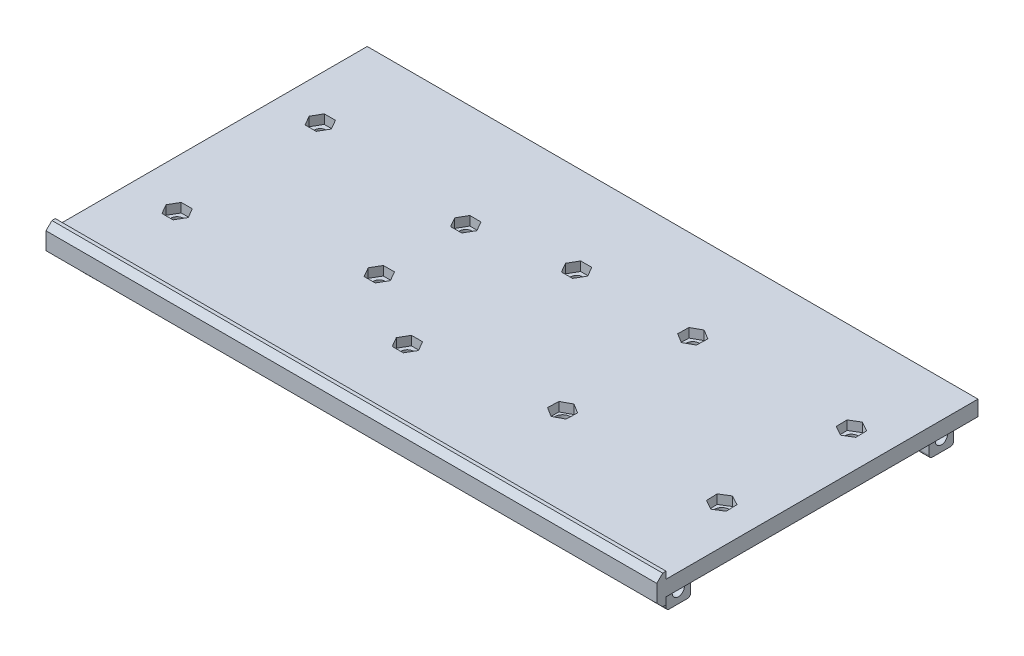
SolidWorks part; units mm, degrees
ref_plane "Alzado" through (0, 0, 0) normal (0, 0, 1) x (1, 0, 0)
ref_plane "Planta" through (0, 0, 0) normal (0, 1, 0) x (1, 0, 0)
ref_plane "Vista lateral" through (0, 0, 0) normal (1, 0, 0) x (0, 0, -1)
sketch "Croquis3" plane through (0, 0, 0) normal (0, 1, 0) x (1, 0, 0)
  line L1 (-116.001, 50) -> (83.999, 50)
  line L2 (-116.001, 50) -> (-116.001, -50)
  line L3 (-116.001, -50) -> (83.999, -50)
  line L4 (83.999, 50) -> (83.999, -50)
  circle A0 centre (19.4896, 21.1007) radius 2.45
  circle A1 centre (71.658, 20.902) radius 2.45
  circle A2 centre (71.3776, -21.3107) radius 2.45
  circle A3 centre (19.1425, -21.1883) radius 2.4502
  dimension "D4" = 4.9
  dimension "D5" = 4.9
  dimension "D6" = 4.9
  dimension "D1" = 100
  dimension "D2" = 50
  dimension "D3" = 200
extrude "Saliente-Extruir1" add sketch "Croquis3" along normal blind 5
sketch "Croquis23" plane through (0, 0, 0) normal (0, 1, 0) x (1, 0, 0)
  line L0 (-116.001, 50) -> (-116.001, -50) construction
  line L1 (-116.001, 23.3955) -> (-13.501, 23.3955) construction
  line L2 (-116.001, 23.3955) -> (-116.001, -30.6045) construction
  line L3 (-116.001, -30.6045) -> (-13.501, -30.6045) construction
  line L4 (-13.501, 23.3955) -> (-13.501, -30.6045) construction
  line L5 (83.999, 50) -> (-116.001, 50) construction
  dimension "D1" = 54
  dimension "D2" = 102.5
  dimension "D3" = 26.6045
sketch "Croquis24" plane through (0, 0, 0) normal (0, 1, 0) x (1, 0, 0)
  circle A0 centre (-18.4173, 20.98) radius 1.9594
  circle A1 centre (-25.0227, -27.8259) radius 1.9784
  circle A2 centre (-49.4418, -12.6126) radius 1.963
  circle A3 centre (-49.4418, 15.7151) radius 2.1255
  circle A4 centre (-102.0965, 20.7097) radius 1.8726
  circle A5 centre (-100.4246, -27.8259) radius 2.0276
sketch "Croquis4" plane through (0, 5, 0) normal (0, 1, 0) x (1, 0, 0)
  circle A0 centre (-18.4173, 20.98) radius 1.9594
  circle A1 centre (-49.4418, 15.7151) radius 2.1255
  circle A2 centre (-49.4418, -12.6126) radius 1.963
  circle A3 centre (-25.0227, -27.8259) radius 1.9784
  circle A4 centre (-100.4246, -27.8259) radius 2.0276
  circle A5 centre (-102.0965, 20.7097) radius 1.8726
  circle A6 centre (-102.0965, 20.7097) radius 3.3726
  circle A7 centre (-100.4246, -27.8259) radius 3.5276
  circle A8 centre (-49.4418, -12.6126) radius 3.463
  circle A9 centre (-25.0227, -27.8259) radius 3.4784
  circle A10 centre (-18.4173, 20.98) radius 3.4594
  circle A11 centre (-49.4418, 15.7151) radius 3.6255
  circle A95 centre (19.4896, 21.1007) radius 2.1242
  circle A96 centre (71.658, 20.902) radius 2.0314
  circle A97 centre (71.3776, -21.3107) radius 2.2649
  circle A98 centre (19.1425, -21.1883) radius 2.4502
  circle A104 centre (19.1425, -21.1883) radius 4.4502
  circle A105 centre (19.4896, 21.1007) radius 4.1242
  circle A106 centre (71.658, 20.902) radius 4.0314
  circle A107 centre (71.3776, -21.3107) radius 4.2649
  dimension "D1" = 2
  dimension "D2" = 1.5
extrude "Saliente-Extruir2" add sketch "Croquis4" against normal blind 9
sketch "Croquis7" plane through (83.999, 0, 0) normal (1, 0, 0) x (0, 0, -1)
  line L0 (-50, 0) -> (50, 0) construction
  line L1 (-50, -7.5) -> (-70, -7.5) construction
  line L2 (-50, -7.5) -> (-50, 12.5) construction
  line L3 (-50, 12.5) -> (-70, 12.5) construction
  line L4 (-70, -7.5) -> (-70, 12.5) construction
  line L5 (-50, 5) -> (-50, 0) construction
  dimension "D1" = 7.5
  dimension "D2" = 20
  dimension "D3" = 20
sketch "Croquis8" plane through (83.999, 0, 0) normal (1, 0, 0) x (0, 0, -1)
  line L0 (-50, 5) -> (-52.133, 5)
  line L1 (-52.133, 5) -> (-52.133, 7.2643)
  line L2 (-52.133, 7.2643) -> (-53.25, 7.2643)
  line L3 (-53.25, 7.2643) -> (-55.1863, 5.328)
  line L4 (-55.1863, 5.328) -> (-55.1863, -0.328)
  line L5 (-55.1863, 2.5) -> (-37.6856, 2.5) construction
  line L6 (-53.25, -2.2643) -> (-55.1863, -0.328)
  line L7 (-52.133, -2.2643) -> (-53.25, -2.2643)
  line L8 (-52.133, 0) -> (-52.133, -2.2643)
  line L9 (-50, 0) -> (-52.133, 0)
  line L10 (-50, 5) -> (-50, 0)
extrude "Saliente-Extruir3" add sketch "Croquis8" against normal blind 200
sketch "Croquis9" plane through (0, 0, 0) normal (0, -1, 0) x (1, 0, 0)
  line L0 (-116.001, 52.133) -> (83.999, 52.133) construction
  line L1 (-112.001, 48.133) -> (-107.001, 48.133)
  line L2 (-112.001, 48.133) -> (-112.001, 40.133)
  line L3 (-112.001, 40.133) -> (-107.001, 40.133)
  line L4 (-107.001, 48.133) -> (-107.001, 40.133)
  line L5 (74.999, 40.133) -> (79.999, 40.133)
  line L6 (79.999, 48.133) -> (79.999, 40.133)
  line L7 (74.999, 48.133) -> (79.999, 48.133)
  line L8 (74.999, 48.133) -> (74.999, 40.133)
  line L9 (74.999, -46) -> (79.999, -46)
  line L10 (79.999, -38) -> (79.999, -46)
  line L11 (74.999, -38) -> (79.999, -38)
  line L12 (74.999, -38) -> (74.999, -46)
  line L13 (-112.001, -46) -> (-107.001, -46)
  line L14 (-107.001, -38) -> (-107.001, -46)
  line L15 (-112.001, -38) -> (-107.001, -38)
  line L16 (-112.001, -38) -> (-112.001, -46)
  line L17 (-116.001, -50) -> (-116.001, 52.133) construction
  line L18 (83.999, 52.133) -> (83.999, -50) construction
  line L19 (83.999, -50) -> (-116.001, -50) construction
  dimension "D1" = 8
  dimension "D2" = 5
  dimension "D3" = 4
  dimension "D6" = 4
  dimension "D7" = 4
  dimension "D8" = 4
  dimension "D4" = 2
  dimension "D5" = 2
extrude "Saliente-Extruir4" add sketch "Croquis9" along normal blind 8
fillet "Redondeo1" radius 1 8 edges at (-109.501, -8, 40.133) (-109.501, -8, 48.133) (-109.501, -8, -38) (-109.501, -8, -46) (77.499, -8, -38) (77.499, -8, -46) (77.499, -8, 40.133) (77.499, -8, 48.133)
sketch "Croquis11" plane through (0, 0, 0) normal (0, -1, 0) x (1, 0, 0)
  line L0 (83.999, -50) -> (-116.001, -50) construction
  line L1 (-57.4359, -46) -> (-49.4359, -46)
  line L2 (-57.4359, -46) -> (-57.4359, -40)
  line L3 (-57.4359, -40) -> (-49.4359, -40)
  line L4 (-49.4359, -46) -> (-49.4359, -40)
  line L5 (42.5641, -40) -> (50.5641, -40)
  line L6 (42.5641, -46) -> (50.5641, -46)
  line L7 (42.5641, -46) -> (42.5641, -40)
  line L8 (50.5641, -46) -> (50.5641, -40)
  dimension "D1" = 4
  dimension "D2" = 6
  dimension "D3" = 8
  dimension "D4" = 2
extrude "Saliente-Extruir5" add sketch "Croquis11" along normal blind 8
fillet "Redondeo3" radius 2 4 edges at (-57.4359, -8, -43) (-49.4359, -8, -43) (42.5641, -8, -43) (50.5641, -8, -43)
sketch "Croquis13" plane through (-112.001, 0, 0) normal (-1, 0, 0) x (0, 0, 1)
  line L0 (-42, 0) -> (-42, -8) construction
  line L1 (-38, 0) -> (-46, 0) construction
  line L2 (-39, -8) -> (-45, -8) construction
  line L3 (44.133, 0) -> (44.133, -8) construction
  line L4 (48.133, 0) -> (40.133, 0) construction
  line L5 (47.133, -8) -> (41.133, -8) construction
  circle A0 centre (-42, -4) radius 2
  circle A1 centre (44.133, -4) radius 2
extrude "Cortar-Extruir3" cut sketch "Croquis13" against normal blind 6
sketch "Croquis14" plane through (79.999, 0, 0) normal (1, 0, 0) x (0, 0, -1)
  line L0 (-44.133, 0) -> (-44.133, -8) construction
  line L1 (-48.133, 0) -> (-40.133, 0) construction
  line L2 (-41.133, -8) -> (-47.133, -8) construction
  line L3 (42, 0) -> (42, -8) construction
  line L4 (38, 0) -> (46, 0) construction
  line L5 (45, -8) -> (39, -8) construction
  circle A0 centre (-44.133, -4) radius 2
  circle A1 centre (42, -4) radius 2
extrude "Cortar-Extruir4" cut sketch "Croquis14" against normal blind 6
sketch "Croquis15" plane through (0, 0, -46) normal (0, 0, -1) x (-1, 0, 0)
  line L0 (-46.5641, 0) -> (-46.5641, -8) construction
  line L1 (-42.5641, 0) -> (-50.5641, 0) construction
  line L2 (-44.5641, -8) -> (-48.5641, -8) construction
  line L3 (53.4359, 0) -> (53.4359, -8) construction
  line L4 (57.4359, 0) -> (49.4359, 0) construction
  line L5 (55.4359, -8) -> (51.4359, -8) construction
  circle A0 centre (-46.5641, -4) radius 2
  circle A1 centre (53.4359, -4) radius 2
extrude "Cortar-Extruir5" cut sketch "Croquis15" against normal blind 6
sketch "Croquis16" plane through (-107.001, 0, 0) normal (1, 0, 0) x (0, 0, -1)
  line L1 (38.9766, -5.6909) -> (41.9526, -7.4638)
  line L2 (41.9526, -7.4638) -> (44.976, -5.7729)
  line L3 (44.976, -5.7729) -> (45.0234, -2.3091)
  line L4 (45.0234, -2.3091) -> (42.0474, -0.5362)
  line L5 (42.0474, -0.5362) -> (39.024, -2.2271)
  line L6 (39.024, -2.2271) -> (38.9766, -5.6909)
  line L7 (-47.0396, -5.8845) -> (-43.9543, -7.4595)
  line L8 (-43.9543, -7.4595) -> (-41.0476, -5.575)
  line L9 (-41.0476, -5.575) -> (-41.2263, -2.1155)
  line L10 (-41.2263, -2.1155) -> (-44.3117, -0.5405)
  line L11 (-44.3117, -0.5405) -> (-47.2183, -2.425)
  line L12 (-47.2183, -2.425) -> (-47.0396, -5.8845)
  circle A0 centre (42, -4) radius 3 construction
  circle A1 centre (-44.133, -4) radius 3 construction
  dimension "D1" = 6
  dimension "D2" = 6
extrude "Cortar-Extruir6" cut sketch "Croquis16" against normal blind 2.6
pattern_linear "MatrizL1" count 2 spacing 184.6 along (1, 0, 0) of "Cortar-Extruir6"
sketch "Croquis17" plane through (0, 0, -40) normal (0, 0, 1) x (1, 0, 0)
  line L1 (49.5555, -2.2532) -> (46.5471, -0.5359)
  line L2 (46.5471, -0.5359) -> (43.5556, -2.2827)
  line L3 (43.5556, -2.2827) -> (43.5726, -5.7468)
  line L4 (43.5726, -5.7468) -> (46.5811, -7.4641)
  line L5 (46.5811, -7.4641) -> (49.5725, -5.7173)
  line L6 (49.5725, -5.7173) -> (49.5555, -2.2532)
  circle A0 centre (46.5641, -4) radius 3 construction
  dimension "D1" = 6
extrude "Cortar-Extruir7" cut sketch "Croquis17" against normal blind 2.6
pattern_linear "MatrizL2" count 2 spacing 100 along (-1, 0, 0) of "Cortar-Extruir7"
sketch "Croquis25" plane through (0, 0, 0) normal (0, 1, 0) x (1, 0, 0)
  circle A0 centre (-102.0965, 20.7097) radius 1.8726
  circle A1 centre (-49.4418, 15.7151) radius 2.1255
  circle A2 centre (-18.4173, 20.98) radius 1.9594
  circle A3 centre (-25.0227, -27.8259) radius 1.9784
  circle A4 centre (-49.4418, -12.6126) radius 1.963
  circle A5 centre (-100.4246, -27.8259) radius 2.0276
extrude "Cortar-Extruir8" cut sketch "Croquis25" along normal blind 10
sketch "Croquis26" plane through (0, 0, 0) normal (0, 1, 0) x (1, 0, 0)
  line L1 (-14.78, 20.98) -> (-16.5987, 24.13)
  line L2 (-16.5987, 24.13) -> (-20.236, 24.13)
  line L3 (-20.236, 24.13) -> (-22.0546, 20.98)
  line L4 (-22.0546, 20.98) -> (-20.236, 17.83)
  line L5 (-20.236, 17.83) -> (-16.5987, 17.83)
  line L6 (-16.5987, 17.83) -> (-14.78, 20.98)
  line L7 (-21.3854, -27.8259) -> (-23.204, -24.6759)
  line L8 (-23.204, -24.6759) -> (-26.8413, -24.6759)
  line L9 (-26.8413, -24.6759) -> (-28.66, -27.8259)
  line L10 (-28.66, -27.8259) -> (-26.8413, -30.9759)
  line L11 (-26.8413, -30.9759) -> (-23.204, -30.9759)
  line L12 (-23.204, -30.9759) -> (-21.3854, -27.8259)
  line L13 (-45.8045, -12.6126) -> (-47.6231, -9.4626)
  line L14 (-47.6231, -9.4626) -> (-51.2605, -9.4626)
  line L15 (-51.2605, -9.4626) -> (-53.0791, -12.6126)
  line L16 (-53.0791, -12.6126) -> (-51.2605, -15.7626)
  line L17 (-51.2605, -15.7626) -> (-47.6231, -15.7626)
  line L18 (-47.6231, -15.7626) -> (-45.8045, -12.6126)
  line L19 (-45.8045, 15.7151) -> (-47.6231, 18.8651)
  line L20 (-47.6231, 18.8651) -> (-51.2605, 18.8651)
  line L21 (-51.2605, 18.8651) -> (-53.0791, 15.7151)
  line L22 (-53.0791, 15.7151) -> (-51.2605, 12.5651)
  line L23 (-51.2605, 12.5651) -> (-47.6231, 12.5651)
  line L24 (-47.6231, 12.5651) -> (-45.8045, 15.7151)
  line L25 (-98.4591, 20.7097) -> (-100.2778, 23.8597)
  line L26 (-100.2778, 23.8597) -> (-103.9151, 23.8597)
  line L27 (-103.9151, 23.8597) -> (-105.7338, 20.7097)
  line L28 (-105.7338, 20.7097) -> (-103.9151, 17.5597)
  line L29 (-103.9151, 17.5597) -> (-100.2778, 17.5597)
  line L30 (-100.2778, 17.5597) -> (-98.4591, 20.7097)
  line L31 (-96.7873, -27.8259) -> (-98.606, -24.6759)
  line L32 (-98.606, -24.6759) -> (-102.2433, -24.6759)
  line L33 (-102.2433, -24.6759) -> (-104.0619, -27.8259)
  line L34 (-104.0619, -27.8259) -> (-102.2433, -30.9759)
  line L35 (-102.2433, -30.9759) -> (-98.606, -30.9759)
  line L36 (-98.606, -30.9759) -> (-96.7873, -27.8259)
  line L37 (22.6841, 22.84) -> (19.5805, 24.7368)
  line L38 (19.5805, 24.7368) -> (16.3861, 22.9975)
  line L39 (16.3861, 22.9975) -> (16.2952, 19.3613)
  line L40 (16.2952, 19.3613) -> (19.3987, 17.4645)
  line L41 (19.3987, 17.4645) -> (22.5932, 19.2039)
  line L42 (22.5932, 19.2039) -> (22.6841, 22.84)
  line L43 (74.7683, 22.7878) -> (71.58, 24.5384)
  line L44 (71.58, 24.5384) -> (68.4697, 22.6527)
  line L45 (68.4697, 22.6527) -> (68.5477, 19.0162)
  line L46 (68.5477, 19.0162) -> (71.736, 17.2655)
  line L47 (71.736, 17.2655) -> (74.8463, 19.1513)
  line L48 (74.8463, 19.1513) -> (74.7683, 22.7878)
  line L49 (74.4662, -19.3897) -> (71.2582, -17.6754)
  line L50 (71.2582, -17.6754) -> (68.1696, -19.5964)
  line L51 (68.1696, -19.5964) -> (68.289, -23.2318)
  line L52 (68.289, -23.2318) -> (71.4969, -24.9461)
  line L53 (71.4969, -24.9461) -> (74.5856, -23.025)
  line L54 (74.5856, -23.025) -> (74.4662, -19.3897)
  line L55 (22.3504, -19.4739) -> (19.2617, -17.553)
  line L56 (19.2617, -17.553) -> (16.0538, -19.2674)
  line L57 (16.0538, -19.2674) -> (15.9346, -22.9028)
  line L58 (15.9346, -22.9028) -> (19.0233, -24.8237)
  line L59 (19.0233, -24.8237) -> (22.2312, -23.1092)
  line L60 (22.2312, -23.1092) -> (22.3504, -19.4739)
  circle A0 centre (-18.4173, 20.98) radius 3.15 construction
  circle A1 centre (-25.0227, -27.8259) radius 3.15 construction
  circle A2 centre (-49.4418, -12.6126) radius 3.15 construction
  circle A3 centre (-49.4418, 15.7151) radius 3.15 construction
  circle A4 centre (-102.0965, 20.7097) radius 3.15 construction
  circle A5 centre (-100.4246, -27.8259) radius 3.15 construction
  circle A6 centre (19.4896, 21.1007) radius 3.15 construction
  circle A7 centre (71.658, 20.902) radius 3.15 construction
  circle A8 centre (71.3776, -21.3107) radius 3.15 construction
  circle A9 centre (19.1425, -21.1883) radius 3.15 construction
  dimension "D1" = 6.3
  dimension "D2" = 6.3
  dimension "D3" = 6.3
  dimension "D4" = 6.3
  dimension "D5" = 6.3
  dimension "D6" = 6.3
  dimension "D7" = 6.3
  dimension "D8" = 6.3
  dimension "D9" = 6.3
  dimension "D10" = 6.3
extrude "Cortar-Extruir9" cut sketch "Croquis26" along normal blind 14 from offset 2
chamfer "Chaflán1" distance 1 angle 45 10 edges at (71.3776, -4, 25.5756) (71.658, -4, -16.8706) (19.4896, -4, -16.9765) (19.1425, -4, 25.6385) (-25.0227, -4, 31.3043) (-18.4173, -4, -17.5206) (-49.4418, -4, -12.0896) (-49.4418, -4, 16.0756) (-100.4246, -4, 31.3535) (-102.0965, -4, -17.3371)
